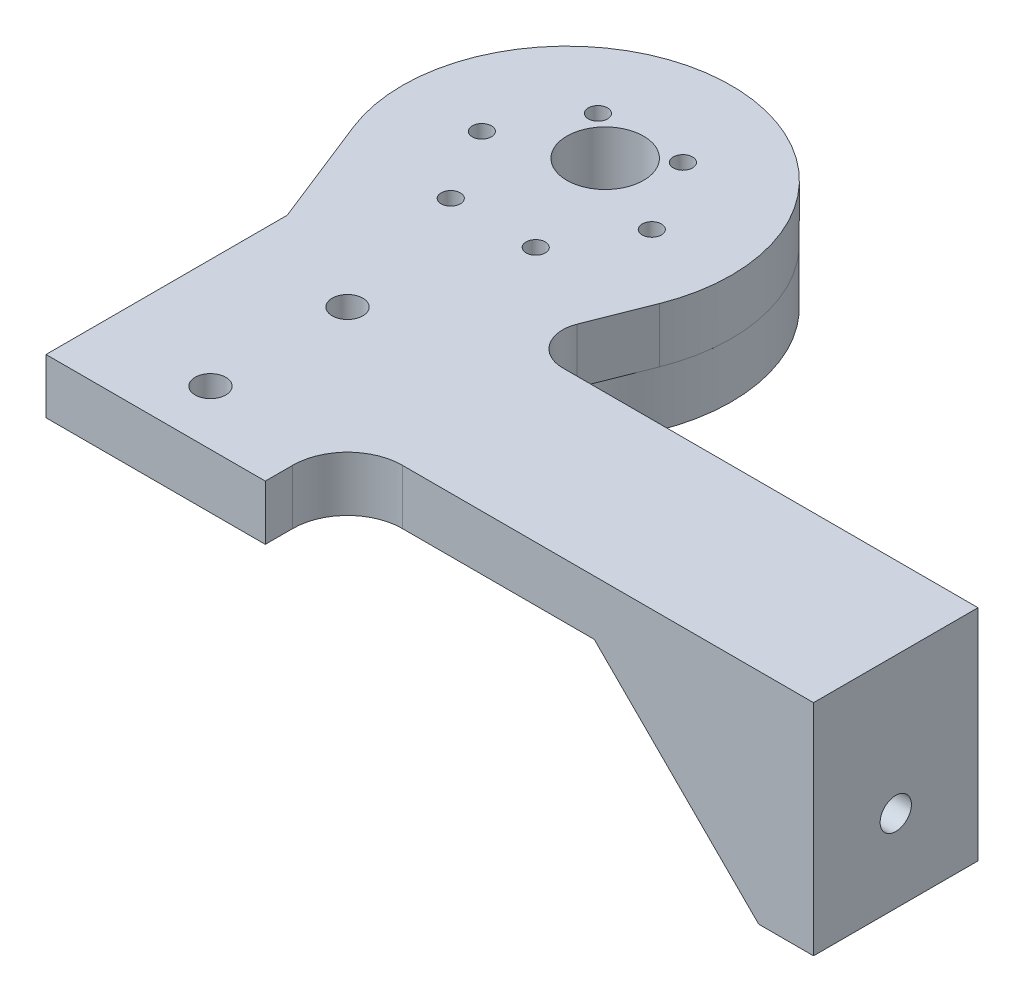
SolidWorks part; units mm, degrees
ref_plane "Front Plane" through (0, 0, 0) normal (0, 0, 1) x (1, 0, 0)
ref_plane "Top Plane" through (0, 0, 0) normal (0, 1, 0) x (1, 0, 0)
ref_plane "Right Plane" through (0, 0, 0) normal (1, 0, 0) x (0, 0, -1)
sketch "Sketch1" plane through (0, 0, 0) normal (0, 1, 0) x (1, 0, 0)
  line L1 (-20, -39) -> (20, -39)
  line L16 (-27.8972, 24.9656) -> (-20, 5)
  line L18 (27.8969, 24.9656) -> (20, 5.0007)
  line L20 (-20, 5) -> (-20, -39)
  line L21 (20, 5.0007) -> (20, -39)
  circle A2 centre (0, -29) radius 2.8
  circle A6 centre (0, 42.9998) radius 7
  circle A10 centre (15.4999, 36) radius 1.75
  circle A11 centre (7.7499, 22.5766) radius 1.75
  circle A12 centre (-7.7501, 22.5766) radius 1.75
  circle A13 centre (-15.5001, 36) radius 1.75
  circle A14 centre (-7.7501, 49.4234) radius 1.75
  circle A15 centre (7.7499, 49.4234) radius 1.75
  circle A22 centre (0, -4) radius 2.8
  arc A25 (-27.8972, 24.9656) -> (27.8969, 24.9656) centre (-0.0001, 36) cw
  point P0 (0, 0)
  point P32 (-0.0001, 36)
  dimension "D3" = 6
  dimension "5.5" = 5.6
  dimension "D6" = 14
  dimension "D8" = 3.5
  dimension "D10" = 25
  dimension "D9" = 39
  dimension "D4" = 5.6
  dimension "D1" = 40
  dimension "D7" = 10
extrude "Boss-Extrude1" add sketch "Sketch1" along normal blind 10
sketch "Sketch2" plane through (0, 0, 0) normal (0, -1, 0) x (1, 0, 0)
  circle A0 centre (-0.0001, -35.9998) radius 30
  circle A1 centre (0, -42.9998) radius 7 construction
  circle A2 centre (-0.0001, -35.9998) radius 18.7
  dimension "D1" = 60
  dimension "D2" = 37.4
extrude "Boss-Extrude2" add sketch "Sketch2" along normal blind 10
ref_plane "Plane1" through (0, 0, 9) normal (0, 0, 1) x (1, 0, 0)
sketch "Sketch3" plane through (0, 0, 9) normal (0, 0, 1) x (1, 0, 0)
  line L0 (20, 10) -> (105, 10)
  line L1 (105, 10) -> (105, -30)
  line L2 (105, -30) -> (95, -30)
  line L3 (95, -30) -> (95, -3.5355)
  line L4 (95, -3.5355) -> (91.4645, 0)
  line L5 (91.4645, 0) -> (20, 0)
  line L6 (20, 0) -> (20, 10)
  dimension "D1" = 85
  dimension "D2" = 10
  dimension "D3" = 40
  dimension "D4" = 135
  dimension "D5" = 5
extrude "Boss-Extrude3" add sketch "Sketch3" along normal mid plane 30
fillet "Fillet1" radius 10 1 edges at (20, 5, 24)
fillet "Fillet2" radius 6 1 edges at (20.3953, 5, -6)
sketch "Sketch4" plane through (105, 0, 0) normal (1, 0, 0) x (0, 0, -1)
  line L0 (-24, -30) -> (6, -30) construction
  circle A0 centre (-9, -15) radius 2.85
  dimension "D1" = 5.7
  dimension "D2" = 15
extrude "Cut-Extrude1" cut sketch "Sketch4" against normal blind 30
sketch "Sketch5" plane through (0, 0, -6) normal (0, 0, -1) x (-1, 0, 0)
  line L0 (-95, -30) -> (-95, 0)
  line L1 (-95, -3.5355) -> (-95, -30) construction
  line L2 (-95, 0) -> (-65, 0)
  line L3 (-29.2208, 0) -> (-91.4645, 0) construction
  line L4 (-65, 0) -> (-95, -30)
  dimension "D1" = 45
  dimension "D2" = 90
  dimension "D3" = 30
extrude "Boss-Extrude4" add sketch "Sketch5" against normal blind 5
mirror "Mirror1" about plane through (0, 0, 9) normal (0, 0, 1) of "Boss-Extrude4"
chamfer "Chamfer1" distance 2.5 angle 45 1 edges at (0, 0, 6.8)
chamfer "Chamfer2" distance 2.5 angle 45 1 edges at (0, 0, 31.8)
